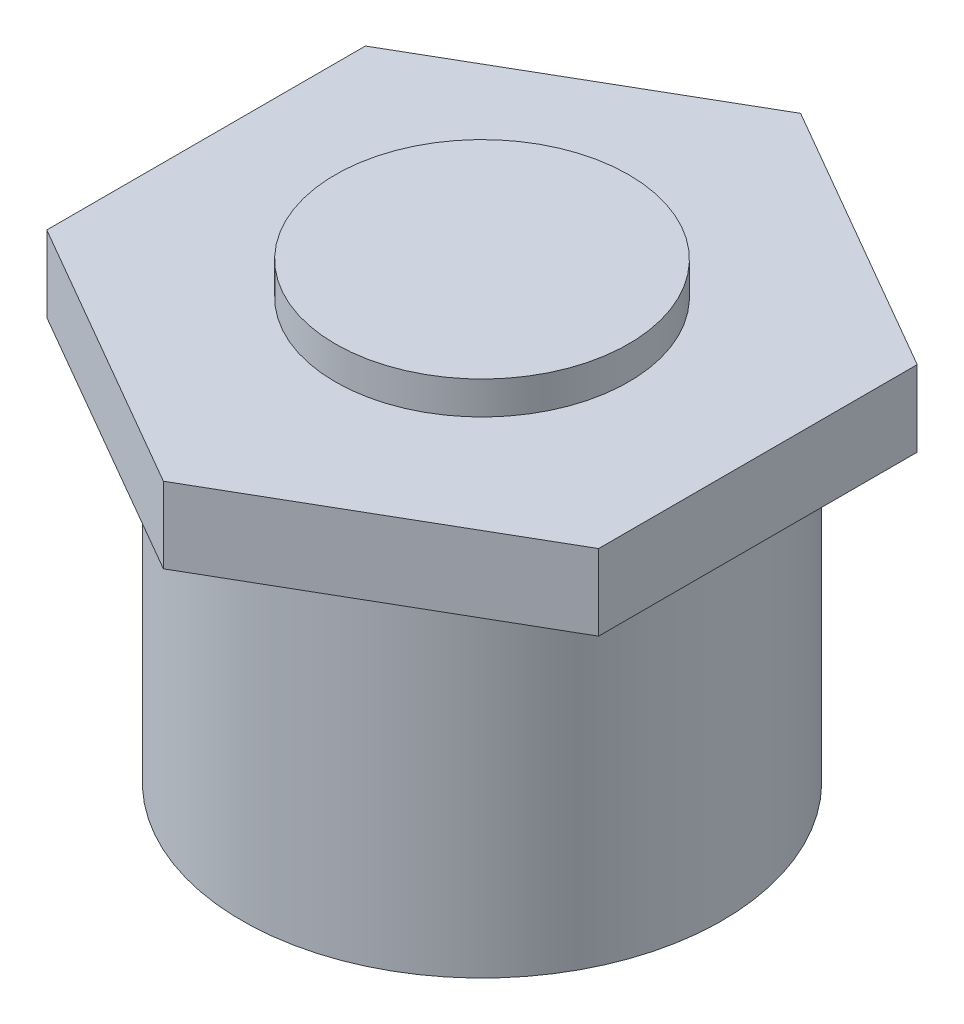
SolidWorks part; units mm, degrees
material "AISI 304"
ref_plane "前视基准面" through (0, 0, 0) normal (0, 0, 1) x (1, 0, 0)
ref_plane "上视基准面" through (0, 0, 0) normal (0, 1, 0) x (1, 0, 0)
ref_plane "右视基准面" through (0, 0, 0) normal (1, 0, 0) x (0, 0, -1)
other "Configuration Table"
sketch "草图1" plane through (0, 0, 0) normal (0, 1, 0) x (1, 0, 0)
  line L0 (0, 0) -> (0, 18.1348) construction
  line L2 (0, 12.6) -> (-10.9119, 6.3)
  line L3 (-10.9119, 6.3) -> (-10.9119, -6.3)
  line L4 (-10.9119, -6.3) -> (0, -12.6)
  line L5 (0, -12.6) -> (10.9119, -6.3)
  line L6 (10.9119, -6.3) -> (10.9119, 6.3)
  line L7 (10.9119, 6.3) -> (0, 12.6)
  circle A0 centre (0, 0) radius 10.9119 construction
  point P3 (0, 12.6)
  dimension "D1" = 25.2
extrude "凸台-拉伸1" add sketch "草图1" along normal blind 3
sketch "草图2" plane through (0, 0, 0) normal (0, -1, 0) x (1, 0, 0)
  circle A0 centre (0, 0) radius 9.5
  dimension "D1" = 19
extrude "凸台-拉伸2" add sketch "草图2" along normal blind 13.6
sketch "草图3" plane through (0, 3, 0) normal (0, 1, 0) x (1, 0, 0)
  circle A0 centre (0, 0) radius 5.8
  dimension "D1" = 11.6
extrude "凸台-拉伸3" add sketch "草图3" along normal blind 1.3
